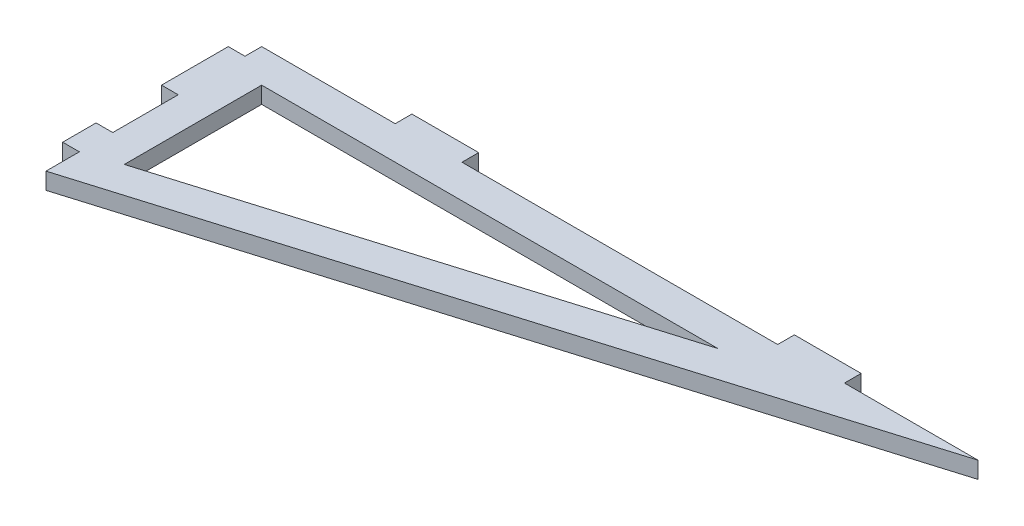
SolidWorks part; units mm, degrees
ref_plane "Front Plane" through (0, 0, 0) normal (0, 0, 1) x (1, 0, 0)
ref_plane "Top Plane" through (0, 0, 0) normal (0, 1, 0) x (1, 0, 0)
ref_plane "Right Plane" through (0, 0, 0) normal (1, 0, 0) x (0, 0, -1)
sketch "Sketch1" plane through (0, 0, 0) normal (0, 1, 0) x (1, 0, 0)
  line L0 (68.1228, 20.51) -> (42.7228, 20.51)
  line L1 (-68.1228, 20.51) -> (-68.1228, 17.335)
  line L2 (-68.1228, -20.51) -> (68.1228, 20.51)
  line L3 (-71.2978, 4.635) -> (-71.2978, 17.335)
  line L4 (-71.2978, 17.335) -> (-68.1228, 17.335)
  line L5 (-71.2978, 4.635) -> (-68.1228, 4.635)
  line L6 (-68.1228, -7.81) -> (-71.2978, -7.81)
  line L7 (-71.2978, -7.81) -> (-71.2978, -14.16)
  line L8 (-71.2978, -14.16) -> (-68.1228, -14.16)
  line L9 (-42.7228, 20.51) -> (-42.7228, 23.685)
  line L10 (-42.7228, 23.685) -> (-30.0228, 23.685)
  line L11 (-30.0228, 23.685) -> (-30.0228, 20.51)
  line L12 (30.0228, 20.51) -> (30.0228, 23.685)
  line L13 (30.0228, 23.685) -> (42.7228, 23.685)
  line L14 (42.7228, 23.685) -> (42.7228, 20.51)
  line L15 (-61.7728, 14.16) -> (-61.7728, -11.9666)
  line L16 (-61.7728, -11.9666) -> (25.0053, 14.16)
  line L17 (25.0053, 14.16) -> (-61.7728, 14.16)
  line L18 (-68.1228, 4.635) -> (-68.1228, -7.81)
  line L19 (-42.7228, 20.51) -> (-68.1228, 20.51)
  line L20 (30.0228, 20.51) -> (-30.0228, 20.51)
  line L21 (-68.1228, -14.16) -> (-68.1228, -20.51)
  dimension "D1" = 136.2456
  dimension "D2" = 41.02
  dimension "D3" = 3.175
  dimension "D4" = 3.175
  dimension "D5" = 12.7
  dimension "D6" = 6.35
  dimension "D7" = 6.35
  dimension "D8" = 3.175
  dimension "D9" = 3.175
  dimension "D10" = 3.175
  dimension "D11" = 12.7
  dimension "D12" = 12.7
  dimension "D13" = 25.4
  dimension "D14" = 25.4
  dimension "D15" = 6.35
  dimension "D16" = 6.35
  dimension "D17" = 6.35
  dimension "D18" = 3.175
extrude "Boss-Extrude1" add sketch "Sketch1" along normal blind 3.175
